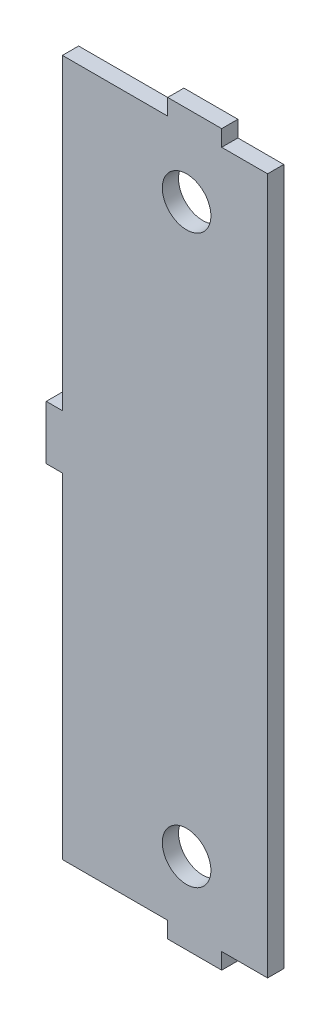
SolidWorks part; units mm, degrees
ref_plane "Front Plane" through (0, 0, 0) normal (0, 0, 1) x (1, 0, 0)
ref_plane "Top Plane" through (0, 0, 0) normal (0, 1, 0) x (1, 0, 0)
ref_plane "Right Plane" through (0, 0, 0) normal (1, 0, 0) x (0, 0, -1)
sketch "Sketch2" plane through (0, 0, 0) normal (0, 0, 1) x (1, 0, 0)
  line L0 (0, 64.5) -> (-8.5, 64.5)
  line L1 (0, 64.5) -> (0, -64.5)
  line L2 (0, -64.5) -> (-8.5, -64.5)
  line L3 (-38, 64.5) -> (-38, 7.5)
  line L4 (-38, -2.5) -> (-38, -64.5)
  line L5 (-38, 7.5) -> (-41, 7.5)
  line L6 (-38, -2.5) -> (-41, -2.5)
  line L7 (-41, 7.5) -> (-41, -2.5)
  line L8 (-18.5, 64.5) -> (-18.5, 67.5)
  line L9 (-18.5, 67.5) -> (-8.5, 67.5)
  line L10 (-8.5, 64.5) -> (-8.5, 67.5)
  line L11 (-18.5, -64.5) -> (-18.5, -67.5)
  line L12 (-18.5, -67.5) -> (-8.5, -67.5)
  line L13 (-8.5, -64.5) -> (-8.5, -67.5)
  line L14 (-18.5, 64.5) -> (-38, 64.5)
  line L15 (-18.5, -64.5) -> (-38, -64.5)
  point P16 (-18.5, -66)
  point P18 (0, 0)
  dimension "D1" = 38
  dimension "D2" = 129
  dimension "D3" = 10
  dimension "D4" = 3
  dimension "D5" = 57
  dimension "D6" = 19.5
extrude "Boss-Extrude1" add sketch "Sketch2" along normal blind 3
sketch "Sketch3" plane through (0, 0, 0) normal (0, 0, 1) x (1, 0, 0)
  line L2 (-18.5, 64.5) -> (-38, 64.5) construction
  line L3 (0, -1.65) -> (0, 1.65) construction
  circle A0 centre (-15, 52.5) radius 4.5
  circle A1 centre (-15, -52.5) radius 4.5
  point P4 (0, 0)
  point P5 (-27.7316, -54.5881)
  dimension "D1" = 9
  dimension "D2" = 105
  dimension "D3" = 15
  dimension "D4" = 12
extrude "Cut-Extrude4" cut sketch "Sketch3" along normal through all
